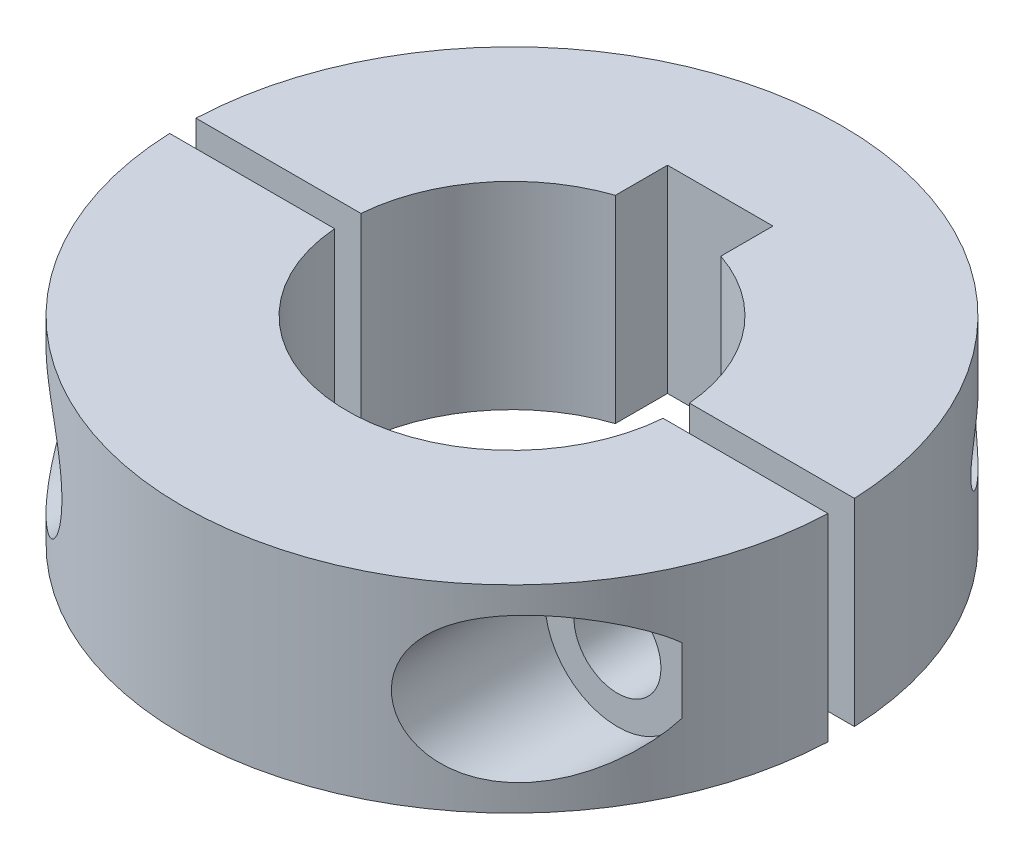
SolidWorks part; units mm, degrees
material "A6061-T6"
ref_plane "前基準面" through (0, 0, 0) normal (0, 0, 1) x (1, 0, 0)
ref_plane "上基準面" through (0, 0, 0) normal (0, 1, 0) x (1, 0, 0)
ref_plane "右基準面" through (0, 0, 0) normal (1, 0, 0) x (0, 0, -1)
sketch "草圖1" plane through (0, 0, 0) normal (0, 1, 0) x (1, 0, 0)
  circle A0 centre (0, 0) radius 25
  circle A1 centre (0, 0) radius 12.5
  dimension "D1" = 25
  dimension "D2" = 50
extrude "填料-伸長1" add sketch "草圖1" along normal mid plane 15
sketch "草圖2" plane through (0, 7.5, 0) normal (0, 1, 0) x (1, 0, 0)
  line L0 (-27.5, 1) -> (27.5, -1) construction
  line L1 (-27.5, 1) -> (27.5, 1)
  line L2 (-27.5, 1) -> (-27.5, -1)
  line L3 (-27.5, -1) -> (27.5, -1)
  line L4 (27.5, 1) -> (27.5, -1)
  dimension "D1" = 2
  dimension "D2" = 55
extrude "除料-伸長1" cut sketch "草圖2" against normal through all
ref_plane "平面1" through (0, 0, 25) normal (0, 0, 1) x (1, 0, 0)
hole_wizard "M6 六角承窩頭蓋螺釘的柱孔4" positions "草圖7" profile "草圖8" counterbore size "M6" standard "ISO"
sketch "草圖7" plane through (0, 0, 25) normal (0, 0, 1) x (1, 0, 0)
  point P0 (-18, 0)
  point P2 (18, 0)
  dimension "D1" = 36
  dimension "D2" = 18
sketch "草圖8" plane through (-18, 0, 25) normal (1, 0, 0) x (0, -1, 0)
  line L0 (0, 0) -> (0, 42.3494)
  line L1 (0, 42.3494) -> (3.3, 42.3494)
  line L3 (3.3, 42.3494) -> (3.3, 15)
  line L4 (3.3, 15) -> (5.5, 15)
  line L5 (5.5, 15) -> (5.5, 0)
  line L7 (5.5, 0) -> (0, 0)
  line L11 (0, -6.35) -> (0, 107.95) construction
  dimension "貫穿孔直徑" = 6.6
  dimension "貫穿孔深度" = 42.3494
  dimension "柱孔直徑" = 11
  dimension "柱孔深度" = 15
hole_wizard "M6 螺紋孔1" positions "草圖9" profile "草圖10" tap size "M6" standard "ISO" end condition through all
sketch "草圖9" plane through (0, 0, -1) normal (0, 0, 1) x (1, 0, 0)
  point P0 (-18, 0)
  point P3 (18, 0)
sketch "草圖10" plane through (-18, 0, -1) normal (1, 0, 0) x (0, -1, 0)
  line L0 (0, 0) -> (0, 24)
  line L1 (0, 24) -> (2.5, 24)
  line L2 (2.5, 24) -> (2.5, 0)
  line L5 (2.5, 0) -> (0, 0)
  line L11 (0, -6.35) -> (0, 107.95) construction
  dimension "貫穿螺孔鑽直徑" = 5
  dimension "貫穿螺孔鑽深度" = 24
cosmetic thread "鑽孔螺紋1" parameters "D2"=6
cosmetic thread "鑽孔螺紋2" parameters "D2"=6
sketch "草圖11" plane through (0, 7.5, 0) normal (0, 1, 0) x (1, 0, 0)
  line L1 (-4, 8.8) -> (4, 8.8)
  line L2 (-4, 8.8) -> (-4, 15.8)
  line L3 (-4, 15.8) -> (4, 15.8)
  line L4 (4, 8.8) -> (4, 15.8)
  dimension "D1" = 8
  dimension "D2" = 7
  dimension "D3" = 4
  dimension "D4" = 15.8
extrude "除料-伸長2" cut sketch "草圖11" against normal through all
